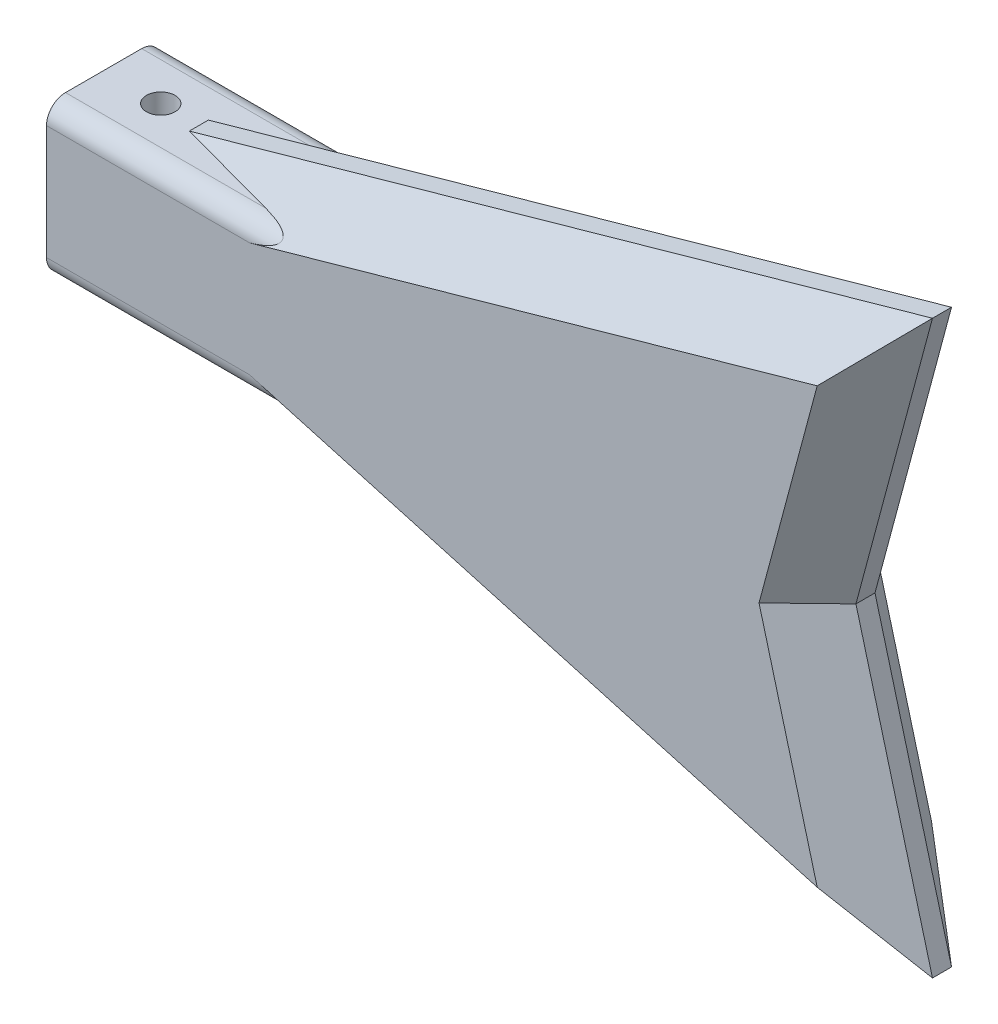
SolidWorks part; units mm, degrees
ref_plane "Ön Düzlem" through (0, 0, 0) normal (0, 0, 1) x (1, 0, 0)
ref_plane "Üst Düzlem" through (0, 0, 0) normal (0, 1, 0) x (1, 0, 0)
ref_plane "Sağ Düzlem" through (0, 0, 0) normal (1, 0, 0) x (0, 0, -1)
sketch "Sketch1" plane through (0, 0, 0) normal (0, 0, 1) x (1, 0, 0)
  line L4 (10, -8) -> (88.0385, -30)
  line L5 (88.0385, -30) -> (80, 0)
  line L7 (10, -8) -> (0, -8)
  line L8 (0, -8) -> (0, 8)
  line L10 (80, 0) -> (0, 0) construction
  line L11 (10, 8) -> (0, 8)
  line L12 (10, 8) -> (88.0385, 30)
  line L13 (88.0385, 30) -> (80, 0)
  dimension "D1" = 80
  dimension "D2" = 8
  dimension "D3" = 30
  dimension "D4" = 105
  dimension "D5" = 10
extrude "Boss-Extrude8" add sketch "Sketch1" along normal mid plane 12
sketch "Sketch7" plane through (0, 0, 0) normal (-1, 0, 0) x (0, 0, 1)
  circle A0 centre (0, 0) radius 5
  dimension "D1" = 10
extrude "Cut-Extrude3" cut sketch "Sketch7" against normal blind 14
sketch "Sketch8" plane through (0, 8, 0) normal (0, 1, 0) x (1, 0, 0)
  line L0 (0, -6) -> (0, 6) construction
  circle A0 centre (6, 0) radius 1.5
  dimension "D1" = 3
  dimension "D2" = 6
extrude "Cut-Extrude4" cut sketch "Sketch8" against normal through all
chamfer "Chamfer3" distance 5 angle 45 8 edges at (49.0192, -19, 6) (84.0192, -15, 6) (84.0192, 15, 6) (49.0192, 19, 6) (49.0192, -19, -6) (84.0192, -15, -6) (84.0192, 15, -6) (49.0192, 19, -6)
fillet "Fillet4" radius 2 4 edges at (14.2137, -8, 6) (14.2137, -8, -6) (14.2137, 8, -6) (14.2137, 8, 6)
